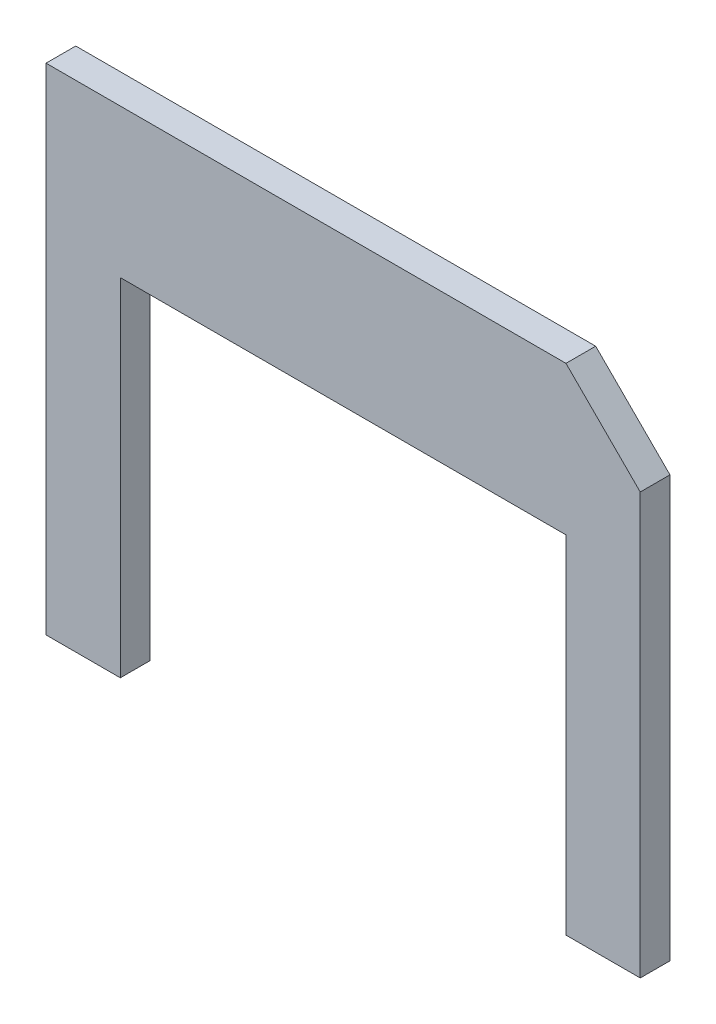
SolidWorks part; units mm, degrees
ref_plane "Front Plane" through (0, 0, 0) normal (0, 0, 1) x (1, 0, 0)
ref_plane "Top Plane" through (0, 0, 0) normal (0, 1, 0) x (1, 0, 0)
ref_plane "Right Plane" through (0, 0, 0) normal (1, 0, 0) x (0, 0, -1)
sketch "Sketch1" plane through (0, 0, 0) normal (0, 0, 1) x (1, 0, 0)
  line L0 (0, 0) -> (0, 10)
  line L1 (0, 10) -> (12, 10)
  line L2 (12, 10) -> (12, 0)
  line L3 (12, 0) -> (10.5, 0)
  line L4 (10.5, 7) -> (10.5, 0)
  line L5 (10.5, 7) -> (1.5, 7)
  line L6 (1.5, 7) -> (1.5, 0)
  line L7 (1.5, 0) -> (0, 0)
  dimension "D1" = 1.5
  dimension "D2" = 12
  dimension "D3" = 1.5
  dimension "D4" = 7
  dimension "D5" = 3
extrude "Boss-Extrude1" add sketch "Sketch1" along normal blind 0.6
sketch "Sketch2" plane through (0, 0, 0.6) normal (0, 0, 1) x (1, 0, 0)
  line L0 (10.5, 10) -> (12, 8.5)
  line L1 (12, 10) -> (0, 10) construction
  line L2 (12, 0) -> (12, 10) construction
  line L3 (12, 8.5) -> (12, 10)
  line L4 (12, 10) -> (10.5, 10)
  dimension "D1" = 1.5
extrude "Cut-Extrude1" cut sketch "Sketch2" against normal through all
